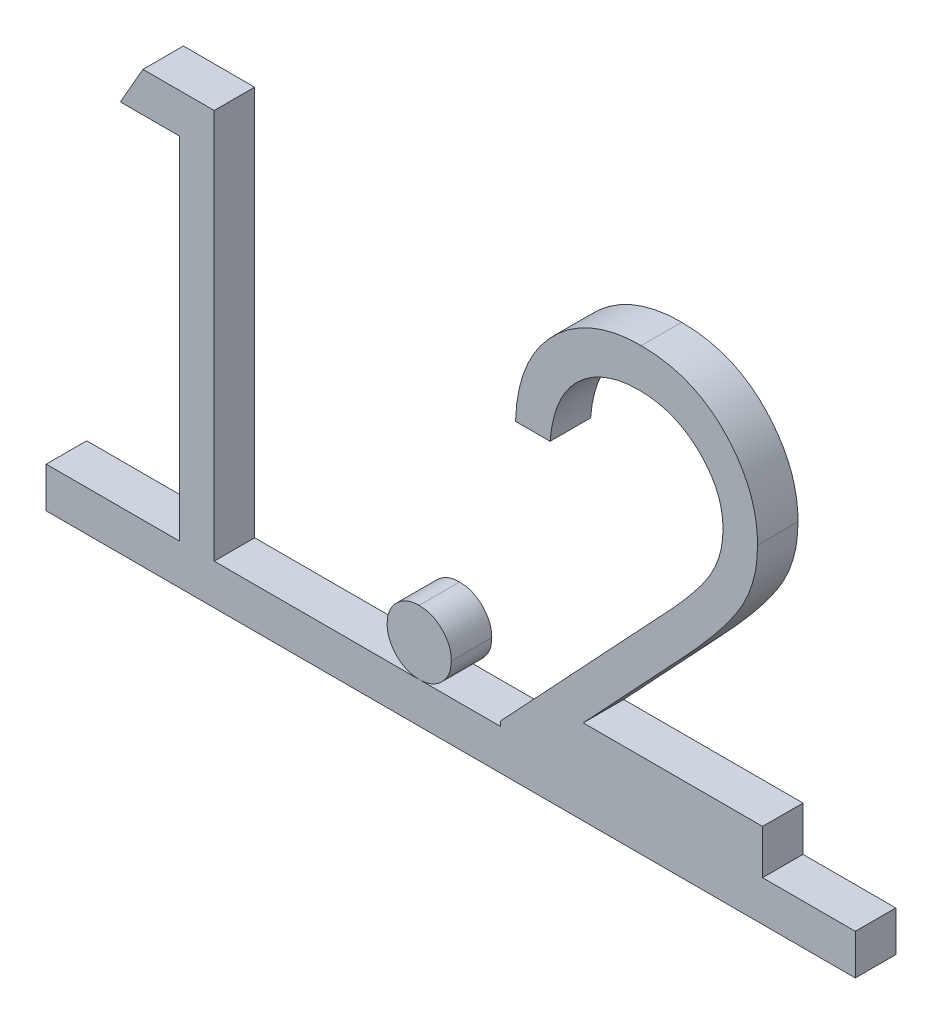
SolidWorks part; units mm, degrees
ref_plane "Front Plane" through (0, 0, 0) normal (0, 0, 1) x (1, 0, 0)
ref_plane "Top Plane" through (0, 0, 0) normal (0, 1, 0) x (1, 0, 0)
ref_plane "Right Plane" through (0, 0, 0) normal (1, 0, 0) x (0, 0, -1)
sketch "Esboço1" plane through (0, 0, 0) normal (0, 0, 1) x (1, 0, 0)
  line L1 (0, 0) -> (0, 4.3189) construction
  text T0 "1.2" font "Century Gothic" height in points 72
extrude "Ressalto-extrusão1" add sketch "Esboço1" along normal blind 2
sketch "Esboço2" plane through (0, 0, 0) normal (1, 0, 0) x (0, 0, -1)
  line L1 (-2, -2.2442) -> (0, -2.2442)
  line L2 (-2, -2.2442) -> (-2, -0.2442)
  line L3 (-2, -0.2442) -> (0, -0.2442)
  line L4 (0, -2.2442) -> (0, -0.2442)
  line L5 (-2, -2.2442) -> (0, -0.2442) construction
  line L6 (-2, -0.2442) -> (0, -2.2442) construction
  point P0 (-1, -1.2442)
  point P5 (-0.8166, -1.2604)
  point P6 (0, 0)
  point P9 (0, 0)
  point P12 (0, 0)
  dimension "D1" = 2
extrude "Ressalto-extrusão2" add sketch "Esboço2" along normal blind 40 separate body
sketch "Esboço3" plane through (0, 0, 0) normal (0, -1, 0) x (1, 0, 0)
  line L4 (6.5942, 0) -> (8.3038, 0)
  line L5 (8.3038, 0) -> (8.3038, 2)
  line L6 (8.3038, 2) -> (6.5942, 2)
  line L7 (6.5942, 2) -> (6.5942, 0)
  line L8 (6.5942, 0) -> (8.3038, 0)
  line L9 (8.3038, 0) -> (8.3038, 2)
  line L10 (8.3038, 2) -> (6.5942, 2)
  line L11 (6.5942, 2) -> (6.5942, 0)
  line L12 (22.4692, 0) -> (35.4135, 0)
  line L13 (35.4135, 0) -> (35.4135, 2)
  line L14 (35.4135, 2) -> (22.4692, 2)
  line L15 (22.4692, 2) -> (22.4692, 0)
  line L16 (22.4692, 0) -> (35.4135, 0)
  line L17 (35.4135, 0) -> (35.4135, 2)
  line L18 (35.4135, 2) -> (22.4692, 2)
  line L19 (22.4692, 2) -> (22.4692, 0)
  dimension "D1" = 0
  dimension "D2" = 0
extrude "Ressalto-extrusão3" add sketch "Esboço3" along normal up to surface (0.2442 mm away) up to face at (20, -0.2442, 1)
